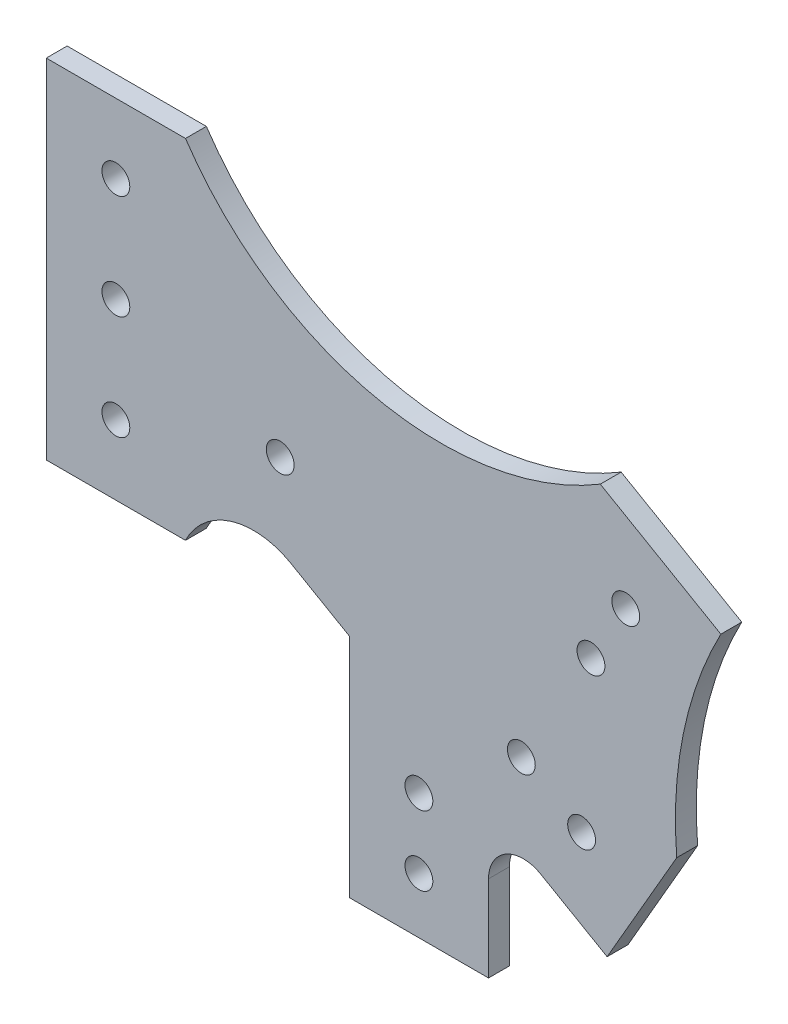
SolidWorks part; units mm, degrees
ref_plane "前视基准面" through (0, 0, 0) normal (0, 0, 1) x (1, 0, 0)
ref_plane "上视基准面" through (0, 0, 0) normal (0, 1, 0) x (1, 0, 0)
ref_plane "右视基准面" through (0, 0, 0) normal (1, 0, 0) x (0, 0, -1)
sketch "草图1" plane through (0, 0, 0) normal (0, 0, 1) x (1, 0, 0)
  line L0 (47.9839, 10.1731) -> (30.6634, 20.1731)
  line L1 (-28.922, 33.3867) -> (-48.922, 33.3867)
  line L2 (-48.922, 33.3867) -> (-48.922, -16.6133)
  line L3 (-48.922, -16.6133) -> (-28.922, -16.6133)
  line L4 (-13.7245, -11.9346) -> (-5.392, -16.7453)
  line L5 (-5.392, -16.7453) -> (-5.392, -49.2923)
  line L6 (-5.392, -49.2923) -> (14.608, -49.2923)
  line L7 (14.608, -49.2923) -> (14.608, -36.9526)
  line L8 (22.108, -32.6225) -> (31.6441, -38.1281)
  line L9 (31.6441, -38.1281) -> (41.6441, -20.8076)
  circle A0 centre (-38.922, 23.3867) radius 2
  circle A1 centre (-38.922, 8.3867) radius 2
  circle A2 centre (-38.922, -6.6133) radius 2
  circle A3 centre (-15.3174, 0.5321) radius 2
  arc A4 (47.9839, 10.1731) -> (41.6441, -20.8076) centre (97.8922, -16.1789) ccw
  arc A5 (-28.922, 33.3867) -> (30.6634, 20.1731) centre (7.8079, 58.0626) ccw
  arc A6 (-13.7245, -11.9346) -> (-28.922, -16.6133) centre (-19.1502, -21.3322) ccw
  arc A7 (22.108, -32.6225) -> (14.608, -36.9526) centre (19.608, -36.9526) ccw
  circle A8 centre (34.3236, 6.5129) radius 2
  circle A9 centre (29.3236, -2.1474) radius 2
  circle A10 centre (19.3236, -19.4679) radius 2
  circle A11 centre (27.9839, -24.4679) radius 2
  circle A12 centre (4.608, -31.2923) radius 2
  circle A13 centre (4.608, -41.2923) radius 2
  dimension "D1" = 4
  dimension "D2" = 4
  dimension "D3" = 4
extrude "凸台-拉伸1" add sketch "草图1" along normal blind 3
